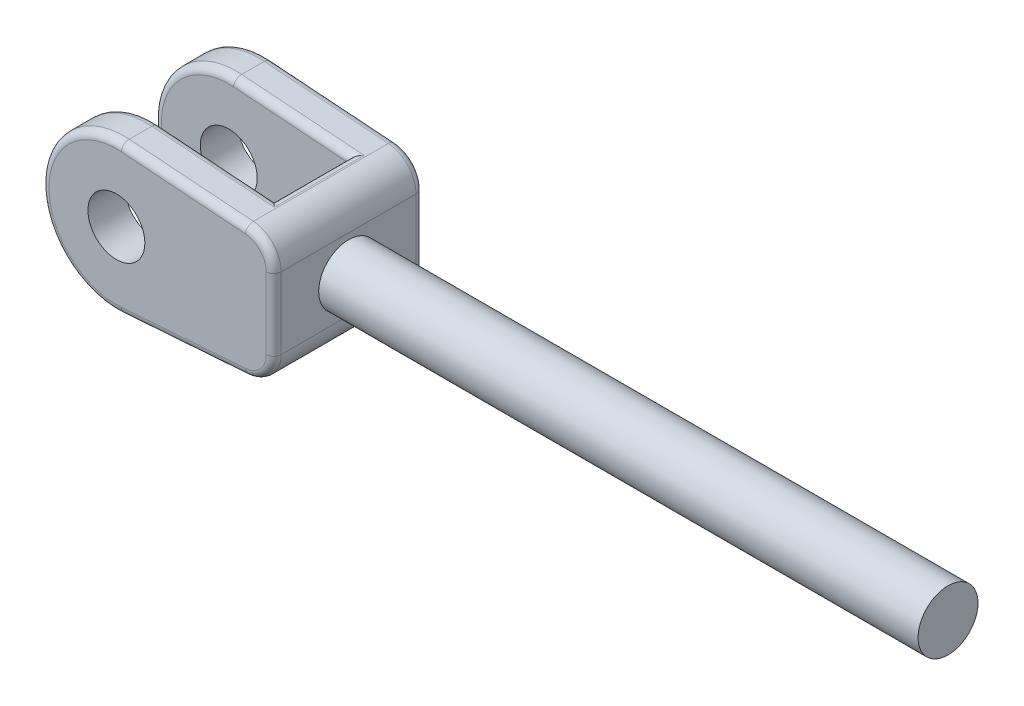
SolidWorks part; units mm, degrees
ref_plane "Front Plane" through (0, 0, 0) normal (0, 0, 1) x (1, 0, 0)
ref_plane "Top Plane" through (0, 0, 0) normal (0, 1, 0) x (1, 0, 0)
ref_plane "Right Plane" through (0, 0, 0) normal (1, 0, 0) x (0, 0, -1)
sketch "Sketch1" plane through (0, 0, 0) normal (1, 0, 0) x (0, 0, -1)
  circle A0 centre (0, 0) radius 1
  dimension "D1" = 2
extrude "Boss-Extrude1" add sketch "Sketch1" along normal blind 20
sketch "Sketch2" plane through (0, 0, 0) normal (0, 0, 1) x (1, 0, 0)
  line L0 (0, 0) -> (-7.75, 0) construction
  line L1 (0, -2.125) -> (0, 2.125)
  line L2 (0, 2.125) -> (-5.0688, 2.4934)
  line L3 (0, -2.125) -> (-5.0688, -2.4934)
  circle A0 centre (-5.25, 0) radius 0.95
  arc A1 (-5.0688, 2.4934) -> (-5.0688, -2.4934) centre (-5.25, 0) ccw
  dimension "D2" = 5
  dimension "D3" = 1.9
  dimension "D1" = 7.75
  dimension "D4" = 4.25
extrude "Boss-Extrude2" add sketch "Sketch2" along normal mid plane 5
sketch "Sketch3" plane through (0, 0, 0) normal (0, 1, 0) x (1, 0, 0)
  line L0 (0, 0) -> (-11.5132, 0) construction
  line L1 (-7.75, 2.5) -> (-7.75, -2.5) construction
  line L2 (-1.25, -1.25) -> (-7.75, -1.25)
  line L3 (-1.25, -1.25) -> (-1.25, 1.25)
  line L4 (-1.25, 1.25) -> (-7.75, 1.25)
  line L5 (-7.75, -1.25) -> (-7.75, 1.25)
  line L6 (-1.25, -1.25) -> (-7.75, 1.25) construction
  line L7 (-1.25, 1.25) -> (-7.75, -1.25) construction
  line L8 (-5.0688, 2.5) -> (-7.75, 2.5) construction
  line L9 (0, -2.5) -> (0, 2.5) construction
  point P3 (-4.5, 0)
  dimension "D1" = 1.25
  dimension "D2" = 1.25
extrude "Cut-Extrude1" cut sketch "Sketch3" against normal through all both and the other way through all
fillet "Fillet1" radius 1 2 edges at (0, 2.125, 0) (0, -2.125, 0)
fillet "Fillet2" radius 0.25 20 edges at (-3.1594, 2.3546, 1.25) (-7.75, 0, 1.25) (-7.75, 0, -2.5) (-2.9981, 2.3429, -2.5) (-0.2677, 1.876, -2.5) (0, 0, -2.5) (-0.2677, -1.876, -2.5) (-3.1594, 2.3546, -1.25) (-7.75, 0, -1.25) (-7.75, 0, 2.5) (-2.9981, 2.3429, 2.5) (-0.2677, 1.876, 2.5) (0, 0, 2.5) (-0.2677, -1.876, 2.5) (-1.25, -2.2159, 0) (-1.25, 2.2159, 0) (-3.1594, -2.3546, 1.25) (-2.9981, -2.3429, -2.5) (-3.1594, -2.3546, -1.25) (-2.9981, -2.3429, 2.5)
